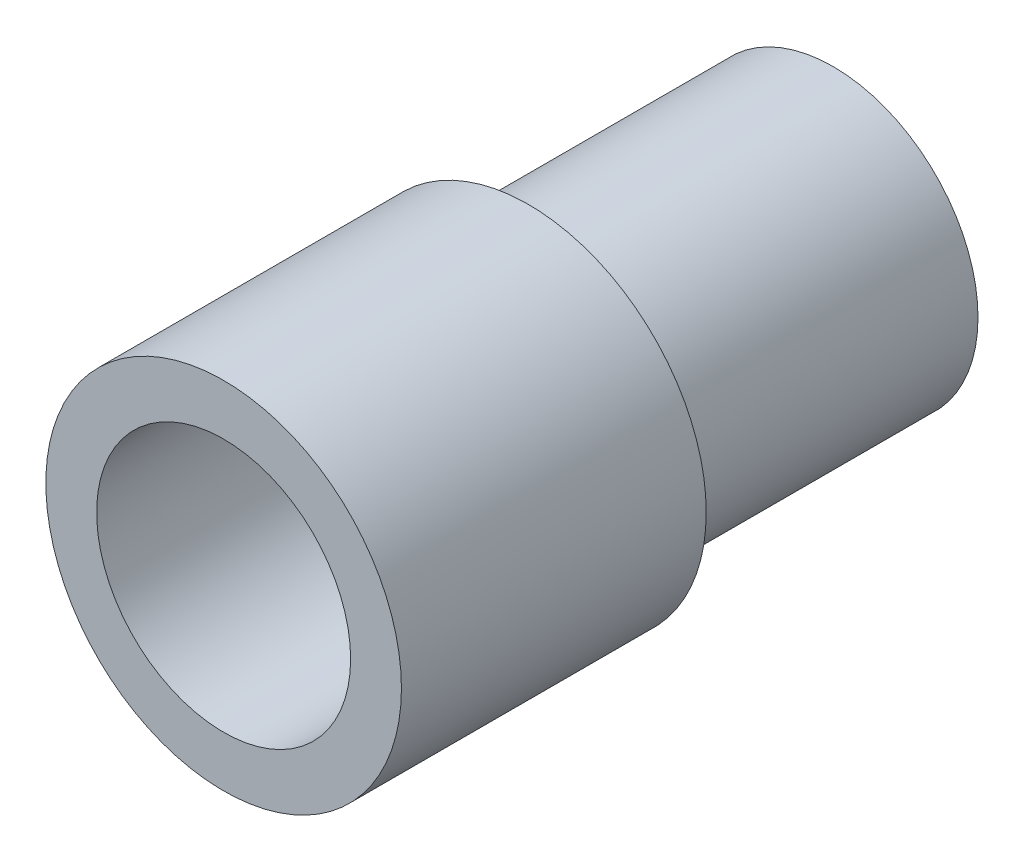
SolidWorks part; units mm, degrees
ref_plane "Front Plane" through (0, 0, 0) normal (0, 0, 1) x (1, 0, 0)
ref_plane "Top Plane" through (0, 0, 0) normal (0, 1, 0) x (1, 0, 0)
ref_plane "Right Plane" through (0, 0, 0) normal (1, 0, 0) x (0, 0, -1)
sketch "Sketch1" plane through (0, 0, 0) normal (0, 0, 1) x (1, 0, 0)
  circle A0 centre (0, 0) radius 4.445
  circle A1 centre (0, 0) radius 3.175
  dimension "D1" = 1.27
  dimension "D2" = 6.35
extrude "Boss-Extrude1" add sketch "Sketch1" along normal blind 7.62
sketch "Sketch2" plane through (0, 0, 0) normal (0, 0, -1) x (-1, 0, 0)
  circle A0 centre (0, 0) radius 1.5875
  circle A1 centre (0, 0) radius 3.6195
  dimension "D1" = 2.032
  dimension "D2" = 3.175
extrude "Boss-Extrude2" add sketch "Sketch2" along normal blind 7.62
